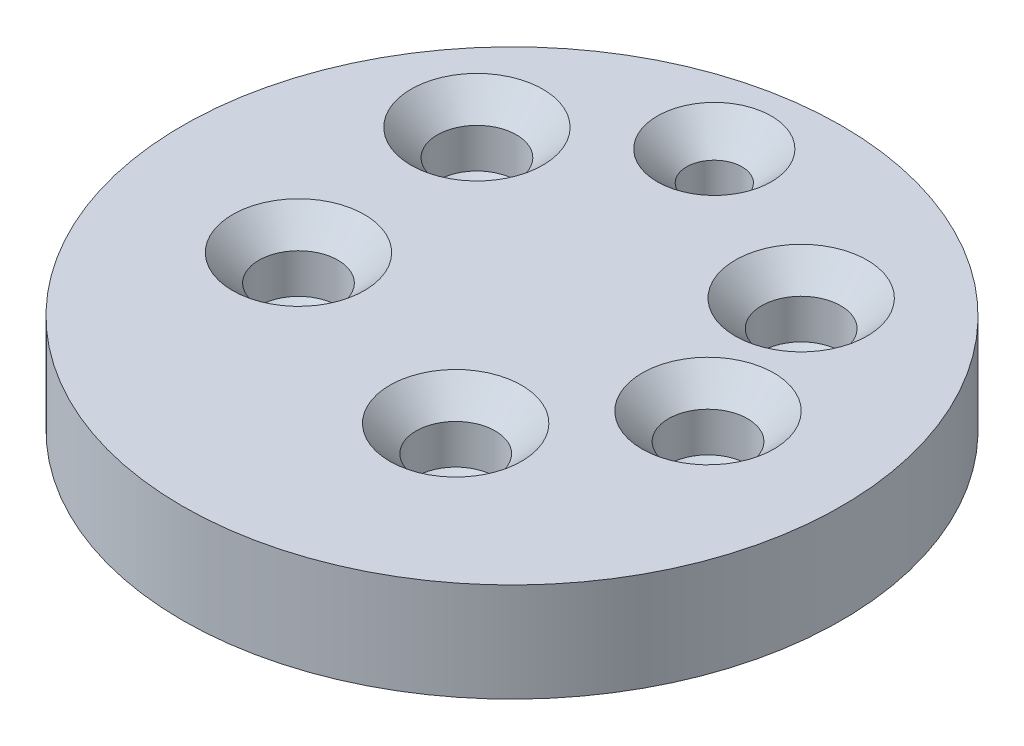
SolidWorks part; units mm, degrees
ref_plane "Front Plane" through (0, 0, 0) normal (0, 0, 1) x (1, 0, 0)
ref_plane "Top Plane" through (0, 0, 0) normal (0, 1, 0) x (1, 0, 0)
ref_plane "Right Plane" through (0, 0, 0) normal (1, 0, 0) x (0, 0, -1)
sketch "Sketch1" plane through (0, 0, 0) normal (0, 1, 0) x (1, 0, 0)
  circle A0 centre (0, 0) radius 50
  dimension "D1" = 100
extrude "Boss-Extrude1" add sketch "Sketch1" along normal blind 15
hole_wizard "CSK for M10 Countersunk Flat Head Screw2" positions "Sketch3" profile "Sketch4" countersink size "M10" standard "DIN"
sketch "Sketch3" plane through (0, 15, 0) normal (0, 1, 0) x (1, 0, 0)
  point P0 (-27.4586, 22.1361)
  point P2 (19.5937, 24.2811)
  point P4 (-24.5219, -7.8728)
  point P6 (9.8324, -18.3768)
  point P8 (27.3677, 2.3731)
sketch "Sketch4" plane through (-27.4586, 15, -22.1361) normal (1, 0, 0) x (0, 0, 1)
  line L0 (0, 0) -> (0, 13.6052)
  line L1 (0, 13.6052) -> (6, 10)
  line L2 (6, 10) -> (6, 4)
  line L3 (6, 4) -> (10, 0)
  line L5 (10, 0) -> (0, 0)
  line L6 (-6, 4) -> (-10, 0) construction
  line L10 (0, 13.6052) -> (-6, 10) construction
  line L11 (0, -6.35) -> (0, 107.95) construction
  dimension "Hole Dia." = 12
  dimension "Hole Depth" = 10
  dimension "Near C'Sink Dia." = 20
  dimension "Near C'Sink Angle" = 90
  dimension "Drill Angle" = 118
hole_wizard "CSK for M8 Countersunk Flat Head Screw1" positions "Sketch6" profile "Sketch7" countersink size "M8" standard "DIN"
sketch "Sketch6" plane through (0, 15, 0) normal (0, 1, 0) x (1, 0, 0)
  point P0 (-6.5966, 37.2912)
sketch "Sketch7" plane through (-6.5966, 15, -37.2912) normal (1, 0, 0) x (0, 0, 1)
  line L0 (0, 0) -> (0, 12.5236)
  line L1 (0, 12.5236) -> (4.2, 10)
  line L2 (4.2, 10) -> (4.2, 4.45)
  line L3 (4.2, 4.45) -> (8.65, 0)
  line L5 (8.65, 0) -> (0, 0)
  line L6 (-4.2, 4.45) -> (-8.65, 0) construction
  line L10 (0, 12.5236) -> (-4.2, 10) construction
  line L11 (0, -6.35) -> (0, 107.95) construction
  dimension "Hole Dia." = 8.4
  dimension "Hole Depth" = 10
  dimension "Near C'Sink Dia." = 17.3
  dimension "Near C'Sink Angle" = 90
  dimension "Drill Angle" = 118
